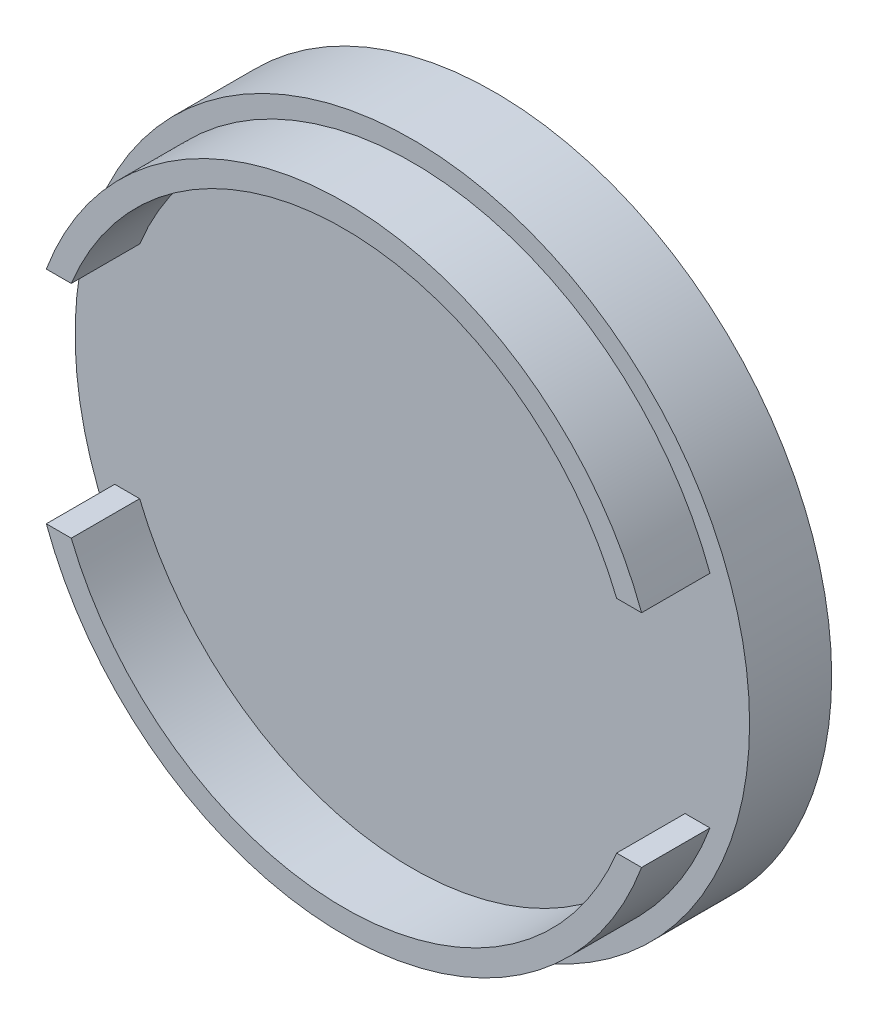
SolidWorks part; units mm, degrees
ref_plane "Front Plane" through (0, 0, 0) normal (0, 0, 1) x (1, 0, 0)
ref_plane "Top Plane" through (0, 0, 0) normal (0, 1, 0) x (1, 0, 0)
ref_plane "Right Plane" through (0, 0, 0) normal (1, 0, 0) x (0, 0, -1)
sketch "Sketch1" plane through (0, 0, 0) normal (0, 0, 1) x (1, 0, 0)
  circle A0 centre (0, 0) radius 24.65
extrude "Boss-Extrude1" add sketch "Sketch1" along normal blind 6
sketch "Sketch2" plane through (0, 0, 6) normal (0, 0, 1) x (1, 0, 0)
  circle A0 centre (0, 0) radius 23.2
  circle A1 centre (0, 0) radius 21.5
extrude "Boss-Extrude2" add sketch "Sketch2" along normal blind 5
sketch "Sketch3" plane through (0, 0, 11) normal (0, 0, 1) x (1, 0, 0)
  line L0 (-21.7546, 8.0609) -> (-19.9317, 8.0609)
  line L2 (21.7546, -8.0609) -> (19.9317, -8.0609)
  line L4 (19.9317, 8.0609) -> (21.7546, 8.0609)
  line L5 (-19.9317, -8.0609) -> (-21.7546, -8.0609)
  circle A0 centre (0, 0) radius 23.2 construction
  circle A1 centre (0, 0) radius 23.2 construction
  arc A2 (-21.7546, 8.0609) -> (-21.7546, -8.0609) centre (0, 0) ccw
  circle A3 centre (0, 0) radius 21.5 construction
  arc A4 (-19.9317, 8.0609) -> (-19.9317, -8.0609) centre (0, 0) ccw
  arc A5 (21.7546, -8.0609) -> (21.7546, 8.0609) centre (0, 0) ccw
  arc A6 (19.9317, -8.0609) -> (19.9317, 8.0609) centre (0, 0) ccw
extrude "Cut-Extrude1" cut sketch "Sketch3" against normal blind 5
